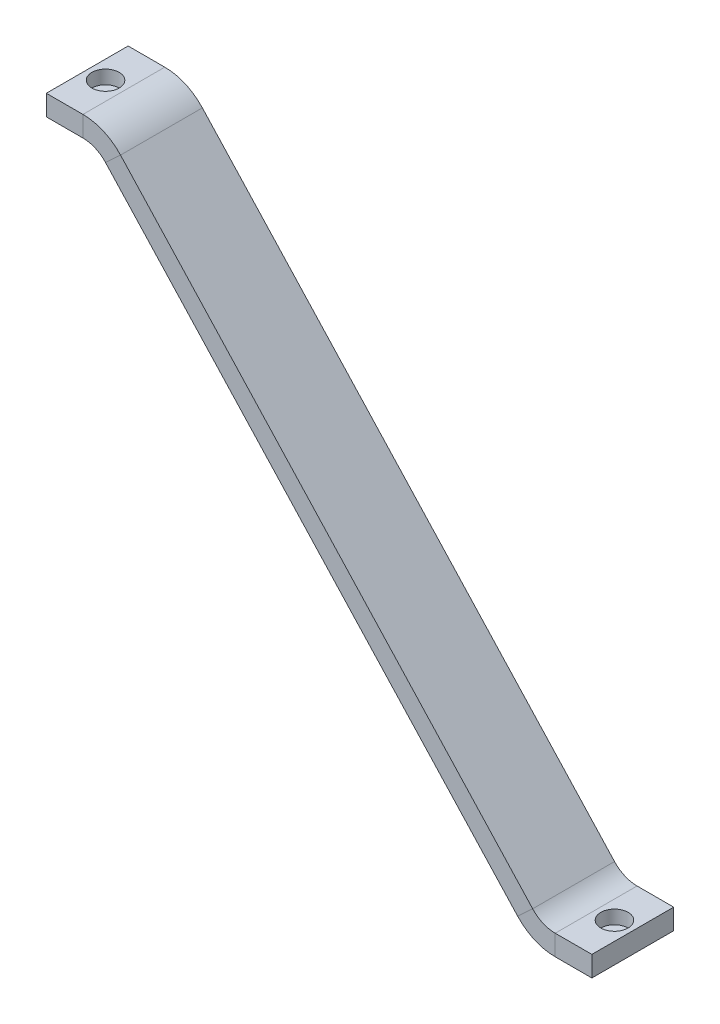
SolidWorks part; units mm, degrees
ref_plane "前视基准面" through (0, 0, 0) normal (0, 0, 1) x (1, 0, 0)
ref_plane "上视基准面" through (0, 0, 0) normal (0, 1, 0) x (1, 0, 0)
ref_plane "右视基准面" through (0, 0, 0) normal (1, 0, 0) x (0, 0, -1)
sketch "草图1" plane through (0, 0, 0) normal (0, 0, 1) x (1, 0, 0)
  line L0 (0, 0) -> (26.8621, 0)
  line L1 (48.9096, -9.6552) -> (351.0904, -337.1255)
  line L2 (373.1379, -346.7807) -> (400, -346.7807)
  arc A0 (351.0904, -337.1255) -> (373.1379, -346.7807) centre (373.1379, -316.7807) ccw
  arc A1 (26.8621, 0) -> (48.9096, -9.6552) centre (26.8621, -30) cw
  point P7 (360, -346.7807)
  point P10 (40, 0)
  dimension "D5" = 30
  dimension "D1" = 40
  dimension "D2" = 40
  dimension "D3" = 400
  dimension "D4" = 132.7
sketch "草图2" plane through (0, 0, 0) normal (1, 0, 0) x (0, 0, -1)
  line L1 (-30, 7.5) -> (30, 7.5)
  line L2 (-30, 7.5) -> (-30, -7.5)
  line L3 (-30, -7.5) -> (30, -7.5)
  line L4 (30, 7.5) -> (30, -7.5)
  line L5 (-30, 7.5) -> (30, -7.5) construction
  line L6 (-30, -7.5) -> (30, 7.5) construction
  point P0 (0, 0)
  dimension "D1" = 60
  dimension "D2" = 15
sweep "扫描1" add profiles "草图2" path "草图1"
sketch "草图3" plane through (0, 7.5, 0) normal (0, 1, 0) x (1, 0, 0)
  line L0 (0, 30) -> (26.8621, 30) construction
  circle A0 centre (13.4311, 0) radius 10
  point P5 (13.4311, 30)
  dimension "D1" = 20
extrude "切除-拉伸1" cut sketch "草图3" against normal blind 10
sketch "草图4" plane through (0, -339.2807, 0) normal (0, 1, 0) x (1, 0, 0)
  line L0 (373.1379, 30) -> (400, 30) construction
  circle A0 centre (386.5689, 0) radius 10
  point P4 (386.5689, 30)
  dimension "D1" = 20
extrude "切除-拉伸2" cut sketch "草图4" against normal blind 10
